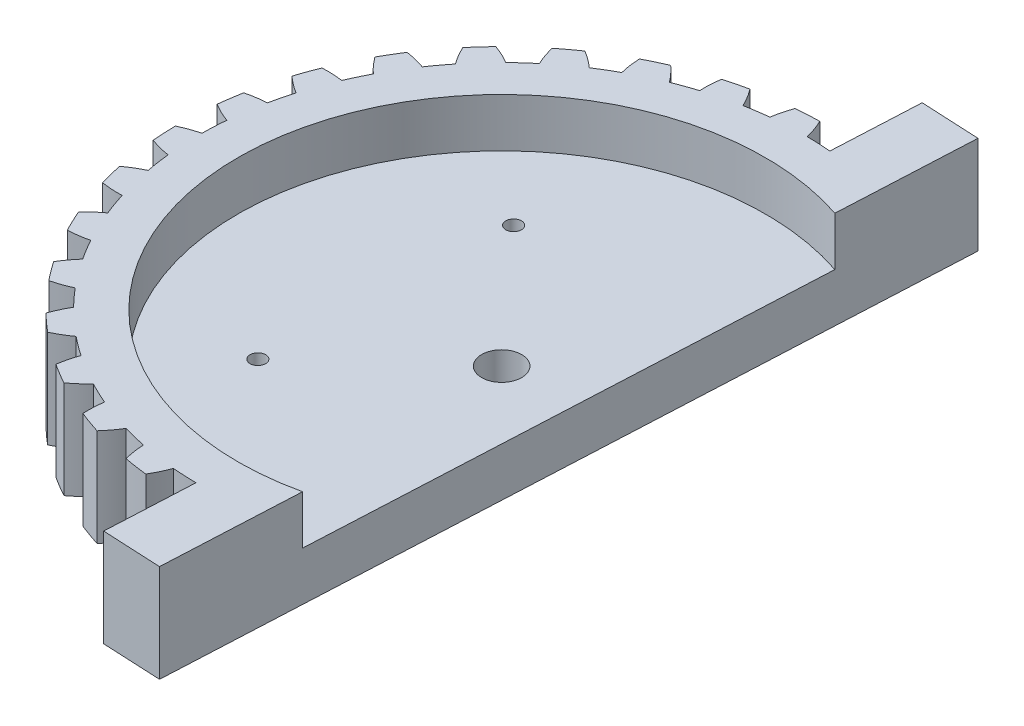
SolidWorks part; units mm, degrees
ref_plane "正面" through (0, 0, 0) normal (0, 0, 1) x (1, 0, 0)
ref_plane "平面" through (0, 0, 0) normal (0, 1, 0) x (1, 0, 0)
ref_plane "右側面" through (0, 0, 0) normal (1, 0, 0) x (0, 0, -1)
sketch "ｽｹｯﾁ1" plane through (0, 0, 0) normal (0, 1, 0) x (1, 0, 0)
  line L0 (0, 0) -> (0, 104.1615) construction
  line L1 (-93.5954, 64) -> (78.777, 64) construction
  line L2 (-63.9379, 40.7285) -> (71.1281, 89.8885) construction
  circle A0 centre (0, 0) radius 64 construction
  circle A1 centre (0, 0) radius 60.1403 construction
  point P7 (0, 64)
  dimension "D1" = 128
  dimension "D2" = 20
sketch "ｽｹｯﾁ2" plane through (0, 0, 0) normal (0, 1, 0) x (1, 0, 0)
  line L0 (-20.5692, 56.5134) -> (0, 64) construction
  line L1 (-14.8381, 58.2811) -> (0.56, 62.2014) construction
  line L2 (-15.8051, 58.0264) -> (0.4905, 62.4649) construction
  line L3 (-16.7677, 57.7555) -> (0.4122, 62.7433) construction
  line L4 (-17.7257, 57.4688) -> (0.3245, 63.0362) construction
  line L5 (-18.6788, 57.1661) -> (0.2269, 63.3434) construction
  line L6 (-19.6267, 56.8476) -> (0.1189, 63.6648) construction
  line L7 (-21.506, 56.1636) -> (-0.1303, 64.3487) construction
  line L8 (-22.4369, 55.7983) -> (-0.2724, 64.7108) construction
  line L9 (-23.3615, 55.4175) -> (-0.4268, 65.0857) construction
  line L10 (-24.2797, 55.0214) -> (-0.594, 65.4734) construction
  line L11 (-25.1912, 54.6101) -> (-0.7745, 65.8733) construction
  line L12 (-26.0957, 54.1837) -> (-0.9688, 66.2852) construction
  line L14 (0, 0) -> (-5.2283, 106.4246) construction
  line L15 (0, 0) -> (0, 104.1615) construction
  circle A0 centre (0, 0) radius 60.1403 construction
  arc A1 (-20.5692, 56.5134) -> (-19.6267, 56.8476) centre (0, 0) cw
  arc A2 (-19.6267, 56.8476) -> (-18.6788, 57.1661) centre (0, 0) cw
  arc A3 (-18.6788, 57.1661) -> (-17.7257, 57.4688) centre (0, 0) cw
  arc A4 (-17.7257, 57.4688) -> (-16.7677, 57.7555) centre (0, 0) cw
  arc A5 (-16.7677, 57.7555) -> (-15.8051, 58.0264) centre (0, 0) cw
  arc A6 (-15.8051, 58.0264) -> (-14.8381, 58.2811) centre (0, 0) cw
  arc A7 (-20.5692, 56.5134) -> (-21.506, 56.1636) centre (0, 0) ccw
  arc A8 (-21.506, 56.1636) -> (-22.4369, 55.7983) centre (0, 0) ccw
  arc A9 (-22.4369, 55.7983) -> (-23.3615, 55.4175) centre (0, 0) ccw
  arc A10 (-23.3615, 55.4175) -> (-24.2797, 55.0214) centre (0, 0) ccw
  arc A11 (-24.2797, 55.0214) -> (-25.1912, 54.6101) centre (0, 0) ccw
  arc A12 (-25.1912, 54.6101) -> (-26.0957, 54.1837) centre (0, 0) ccw
  arc A13 (-20.5692, 56.5134) -> (0.8963, 60.1336) centre (0, 0) cw
  circle A14 centre (0, 0) radius 66 construction
  circle A16 centre (0, 0) radius 64 construction
  spline S0 degree 3 poles (-0.9688, 66.2852) (-0.8394, 66.0167) (-0.6553, 65.6183) (-0.4279, 65.0913) (-0.2734, 64.7163) (-0.1313, 64.3543) (-0.0009, 64.0056) (0.118, 63.6704) (0.226, 63.349) (0.3237, 63.0417) (0.4114, 62.7488) (0.6791, 61.7983) (0.8527, 60.9277) (0.8963, 60.1336) knots 0 0 0 0 0.138368 0.203693 0.266445 0.326623 0.384229 0.439262 0.491722 0.541609 0.588924 0.633665 1 1 1 1
  spline S1 degree 3 poles (-5.533, 66.061) (-5.6354, 65.7811) (-5.7795, 65.3666) (-5.9542, 64.8198) (-6.0712, 64.4315) (-6.1772, 64.0573) (-6.2727, 63.6974) (-6.3582, 63.3522) (-6.4342, 63.0218) (-6.5013, 62.7064) (-6.5599, 62.4063) (-6.7331, 61.4341) (-6.8206, 60.5507) (-6.7861, 59.7562) knots 0 0 0 0 0.138368 0.203693 0.266445 0.326623 0.384229 0.439262 0.491722 0.541609 0.588924 0.633665 1 1 1 1
  dimension "D1" = 21.8893
  dimension "D3" = 19.8893
  dimension "D4" = 20.8893
  dimension "D5" = 18.8893
  dimension "D6" = 17.8893
  dimension "D7" = 16.8893
  dimension "D8" = 15.8893
  dimension "D9" = 22.8893
  dimension "D10" = 23.8893
  dimension "D11" = 24.8893
  dimension "D12" = 25.8893
  dimension "D13" = 26.8893
  dimension "D14" = 27.8893
  dimension "D15" = 2.813
  dimension "D16" = 2
  dimension "D2" = 1
sketch "ｽｹｯﾁ3" plane through (0, 0, 0) normal (0, 1, 0) x (1, 0, 0)
  arc A1 (0.6104, 61.997) -> (-6.6843, 61.6386) centre (0, 0) ccw
  arc A3 (-0.8309, 65.9948) -> (-5.6417, 65.7584) centre (0, 0) ccw
  spline S2 degree 3 poles (-5.533, 66.061) (-5.6354, 65.7811) (-5.7795, 65.3666) (-5.9542, 64.8198) (-6.0712, 64.4315) (-6.1772, 64.0573) (-6.2727, 63.6974) (-6.3582, 63.3522) (-6.4342, 63.0218) (-6.5013, 62.7064) (-6.5599, 62.4063) (-6.7331, 61.4341) (-6.8206, 60.5507) (-6.7861, 59.7562) knots 0 0 0 0 0.138368 0.203693 0.266445 0.326623 0.384229 0.439262 0.491722 0.541609 0.588924 0.633665 1 1 1 1 construction
  spline S3 degree 3 poles (-0.9688, 66.2852) (-0.8394, 66.0167) (-0.6553, 65.6183) (-0.4279, 65.0913) (-0.2734, 64.7163) (-0.1313, 64.3543) (-0.0009, 64.0056) (0.118, 63.6704) (0.226, 63.349) (0.3237, 63.0417) (0.4114, 62.7488) (0.6791, 61.7983) (0.8527, 60.9277) (0.8963, 60.1336) knots 0 0 0 0 0.138368 0.203693 0.266445 0.326623 0.384229 0.439262 0.491722 0.541609 0.588924 0.633665 1 1 1 1 construction
  spline S4 degree 3 poles (-5.6417, 65.7584) (-5.7052, 65.5784) (-5.8121, 65.2645) (-5.9542, 64.8198) (-6.0712, 64.4315) (-6.1772, 64.0573) (-6.2727, 63.6974) (-6.3582, 63.3522) (-6.4342, 63.0218) (-6.5013, 62.7064) (-6.5599, 62.4063) (-6.6229, 62.0526) (-6.6623, 61.7982) (-6.6843, 61.6386) knots 0 0 0 0 0.134544 0.233721 0.328992 0.420358 0.507816 0.591369 0.671015 0.746755 0.818588 0.886516 1 1 1 1
  spline S5 degree 3 poles (-0.8309, 65.9948) (-0.7501, 65.8218) (-0.6129, 65.5199) (-0.4279, 65.0913) (-0.2734, 64.7163) (-0.1313, 64.3543) (-0.0009, 64.0056) (0.118, 63.6704) (0.226, 63.349) (0.3237, 63.0417) (0.4114, 62.7488) (0.5088, 62.4029) (0.573, 62.1536) (0.6104, 61.997) knots 0 0 0 0 0.134544 0.233721 0.328992 0.420358 0.507816 0.591369 0.671015 0.746755 0.818588 0.886516 1 1 1 1
  point P3 (-5.6417, 65.7584)
  point P4 (-0.8309, 65.9948)
  point P5 (0.6104, 61.997)
  point P6 (-6.6843, 61.6386)
  dimension "D1" = 124
  dimension "D2" = 4
sketch "ｽｹｯﾁ5" plane through (0, 0, 0) normal (0, 1, 0) x (1, 0, 0)
  circle A0 centre (0, 0) radius 62
  dimension "D1" = 124
extrude "ﾎﾞｽ - 押し出し5" add sketch "ｽｹｯﾁ5" along normal blind 20
extrude "ﾎﾞｽ - 押し出し6" add sketch "ｽｹｯﾁ3" along normal blind 20
pattern_circular "円形ﾊﾟﾀｰﾝ3" count 32 over 360 about axis through (0, 20, 0) along (0, 1, 0) of "ﾎﾞｽ - 押し出し6"
sketch "ｽｹｯﾁ8" plane through (0, 20, 0) normal (0, 1, 0) x (1, 0, 0)
  circle A0 centre (0, 0) radius 54
  arc A1 (65.9948, 0.8309) -> (65.7584, 5.6417) centre (0, 0) ccw construction
  dimension "D1" = 12
extrude "ｶｯﾄ - 押し出し3" cut sketch "ｽｹｯﾁ8" against normal offset from surface (10 mm away) 10 up to face at (0, 0, 0)
sketch "ｽｹｯﾁ6" plane through (0, 10, 0) normal (0, 1, 0) x (1, 0, 0)
  line L0 (3.0422, 61.9253) -> (-2449.4393, -49859.4828) construction
  line L1 (-1.6969, 0.0834) -> (-49921.7047, 2452.4961) construction
  circle A0 centre (-23.7432, 26.1966) radius 1.6
  circle A9 centre (-26.1966, -23.7432) radius 1.6
  arc A10 (5.4693, 61.7583) -> (0.6104, 61.997) centre (0, 0) ccw construction
  arc A11 (-5.4693, -61.7583) -> (-0.6104, -61.997) centre (0, 0) ccw construction
  arc A12 (-61.7583, 5.4693) -> (-61.997, 0.6104) centre (0, 0) ccw construction
  point P14 (3.0422, 61.9253)
  point P18 (-3.0422, -61.9253)
  point P24 (-61.9253, 3.0422)
  dimension "D5" = 3.2
  dimension "D1" = 25
  dimension "D2" = 25
sketch "ｽｹｯﾁ7" plane through (0, 20, 0) normal (0, 1, 0) x (1, 0, 0)
  line L12 (-61.3112, 3.012) -> (49878.4616, -2450.3717) construction
  line L14 (11.2948, -65.0264) -> (62.7608, -67.5547)
  line L16 (17.6141, 63.6061) -> (69.0802, 61.0778)
  line L19 (69.0802, 61.0778) -> (62.7608, -67.5547)
  line L20 (17.6141, 63.6061) -> (11.2948, -65.0264)
  circle A3 centre (0, 0) radius 66 construction
  circle A5 centre (0, 0) radius 4.1
  arc A6 (-61.7583, 5.4693) -> (-61.997, 0.6104) centre (0, 0) ccw construction
  arc A7 (61.7583, -5.4693) -> (61.997, -0.6104) centre (0, 0) ccw construction
  point P8 (-61.9253, 3.0422)
  point P12 (61.9253, -3.0422)
  dimension "D3" = 132
  dimension "D4" = 8.2
extrude "ｶｯﾄ - 押し出し2" cut sketch "ｽｹｯﾁ7" against normal through all
sketch "ｽｹｯﾁ9" plane through (0, 0, 0) normal (0, 1, 0) x (1, 0, 0)
  line L0 (6.3548, 79.7843) -> (5.0764, 53.7609)
  line L1 (-1.496, -80.023) -> (10.5291, -80.6137)
  line L2 (0, 0) -> (2453.3837, 49939.7728) construction
  line L3 (-61.9253, 3.0422) -> (49877.8475, -2450.3415) construction
  line L4 (10.5291, -80.6137) -> (11.9018, -52.6721)
  line L5 (18.3799, 79.1935) -> (6.3548, 79.7843)
  line L7 (17.0072, 51.2519) -> (11.9018, -52.6721) construction
  line L8 (17.4126, 59.5046) -> (17.0072, 51.2519) construction
  line L9 (-0.2175, -53.9996) -> (-1.496, -80.023)
  line L10 (17.0072, 51.2519) -> (18.3799, 79.1935)
  arc A0 (5.4693, 61.7583) -> (0.6104, 61.997) centre (0, 0) ccw construction
  arc A1 (-61.7583, 5.4693) -> (-61.997, 0.6104) centre (0, 0) ccw construction
  arc A2 (5.0764, 53.7609) -> (17.0072, 51.2519) centre (0, 0) cw
  arc A3 (-0.2175, -53.9996) -> (11.9018, -52.6721) centre (0, 0) ccw
  arc A4 (17.0072, 51.2519) -> (11.9018, -52.6721) centre (0, 0) ccw construction
  arc A5 (17.0072, 51.2519) -> (11.9018, -52.6721) centre (0, 0) ccw construction
  point P14 (3.0422, 61.9253)
  point P20 (-61.9253, 3.0422)
  dimension "D1" = 80
  dimension "D2" = 80
extrude "ｶｯﾄ - 押し出し5" cut sketch "ｽｹｯﾁ6" against normal through all
extrude "ﾎﾞｽ - 押し出し8" add sketch "ｽｹｯﾁ9" along normal up to surface (20 mm away) up to face at (-33.7678, 20, -1.8228)
sketch "ｽｹｯﾁ10" plane through (0, 0, 0) normal (0, -1, 0) x (1, 0, 0)
  circle A0 centre (-26.1966, 23.7432) radius 3
  circle A1 centre (-23.7432, -26.1966) radius 3
  dimension "D1" = 6
extrude "ｶｯﾄ - 押し出し6" cut sketch "ｽｹｯﾁ10" against normal blind 2
equation "\"D3@ｽｹｯﾁ2\"=\"D4@ｽｹｯﾁ2\"-\"D2@ｽｹｯﾁ2\""
equation "\"D4@ｽｹｯﾁ2\"=\"D1@ｽｹｯﾁ2\"-\"D2@ｽｹｯﾁ2\""
equation "\"D5@ｽｹｯﾁ2\"=\"D3@ｽｹｯﾁ2\"-\"D2@ｽｹｯﾁ2\""
equation "\"D6@ｽｹｯﾁ2\"=\"D5@ｽｹｯﾁ2\"-\"D2@ｽｹｯﾁ2\""
equation "\"D7@ｽｹｯﾁ2\"=\"D6@ｽｹｯﾁ2\"-\"D2@ｽｹｯﾁ2\""
equation "\"D8@ｽｹｯﾁ2\"=\"D7@ｽｹｯﾁ2\"-\"D2@ｽｹｯﾁ2\""
equation "\"D9@ｽｹｯﾁ2\"=\"D1@ｽｹｯﾁ2\"+\"D2@ｽｹｯﾁ2\""
equation "\"D10@ｽｹｯﾁ2\"=\"D9@ｽｹｯﾁ2\"+\"D2@ｽｹｯﾁ2\""
equation "\"D11@ｽｹｯﾁ2\"=\"D10@ｽｹｯﾁ2\"+\"D2@ｽｹｯﾁ2\""
equation "\"D12@ｽｹｯﾁ2\"=\"D11@ｽｹｯﾁ2\"+\"D2@ｽｹｯﾁ2\""
equation "\"D13@ｽｹｯﾁ2\"=\"D12@ｽｹｯﾁ2\"+\"D2@ｽｹｯﾁ2\""
equation "\"D14@ｽｹｯﾁ2\"=\"D13@ｽｹｯﾁ2\"+\"D2@ｽｹｯﾁ2\""
equation "\"D15@ｽｹｯﾁ2\"=90/32"
